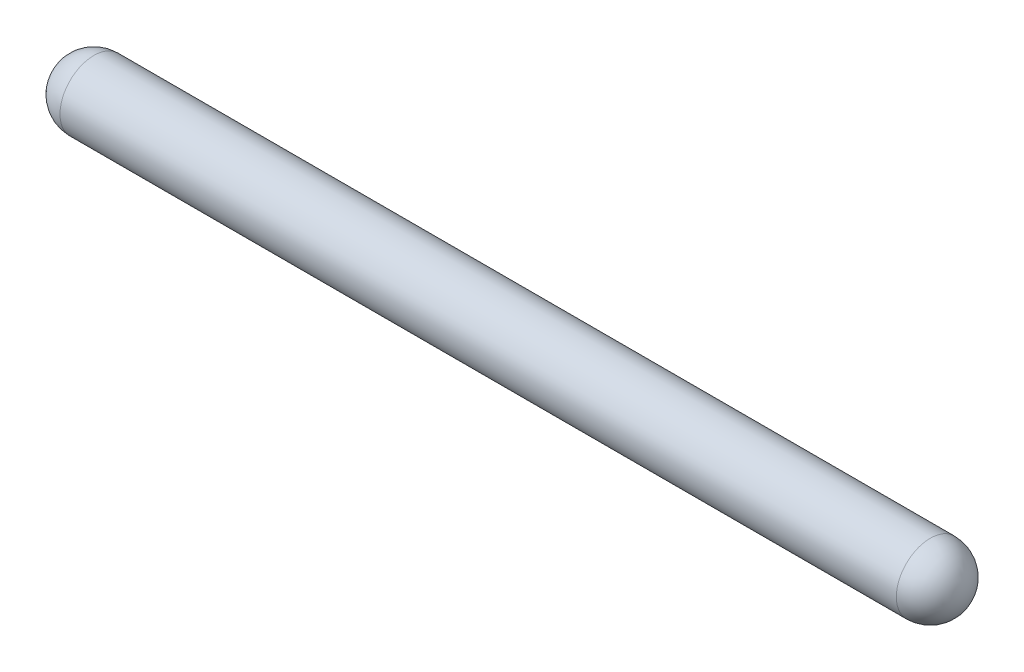
SolidWorks part; units mm, degrees
material "Plain Carbon Steel"
ref_plane "Front Plane" through (0, 0, 0) normal (0, 0, 1) x (1, 0, 0)
ref_plane "Top Plane" through (0, 0, 0) normal (0, 1, 0) x (1, 0, 0)
ref_plane "Right Plane" through (0, 0, 0) normal (1, 0, 0) x (0, 0, -1)
sketch "Sketch1" plane through (0, 0, 0) normal (1, 0, 0) x (0, 0, -1)
  circle A0 centre (0, 0) radius 2.3813
  dimension "D1" = 4.7625
extrude "Boss-Extrude1" add sketch "Sketch1" along normal blind 63.5
fillet "Fillet1" radius 2.3813 2 edges at (0, 0, -2.3813) (63.5, 0, -2.3813)
